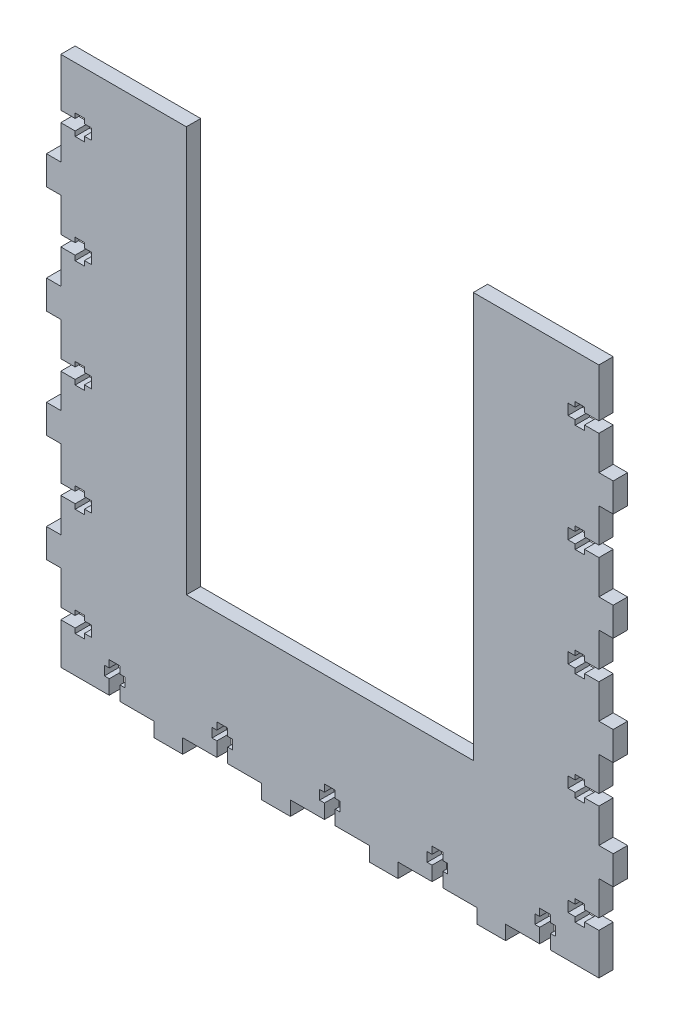
SolidWorks part; units mm, degrees
ref_plane "前视基准面" through (0, 0, 0) normal (0, 0, 1) x (1, 0, 0)
ref_plane "上视基准面" through (0, 0, 0) normal (0, 1, 0) x (1, 0, 0)
ref_plane "右视基准面" through (0, 0, 0) normal (1, 0, 0) x (0, 0, -1)
sketch "草图1" plane through (0, 0, 0) normal (0, 0, 1) x (1, 0, 0)
  line L9 (145, 56.5) -> (149, 56.5)
  line L10 (149, 56.5) -> (149, 55.15)
  line L11 (149, 55.15) -> (151.6, 55.15)
  line L12 (151.6, 55.15) -> (151.6, 56.5)
  line L13 (151.6, 56.5) -> (153.6, 56.5)
  line L14 (153.6, 56.5) -> (153.6, 59.5)
  line L23 (145, 58) -> (143.6922, 58) construction
  line L24 (145, 56.5) -> (145, 47)
  line L25 (151.6, 60.85) -> (151.6, 59.5)
  line L26 (149, 59.5) -> (149, 60.85)
  line L27 (151.6, 59.5) -> (153.6, 59.5)
  line L28 (149, 60.85) -> (151.6, 60.85)
  line L29 (145, 59.5) -> (149, 59.5)
  line L31 (145, 39) -> (141, 39)
  line L32 (141, 39) -> (141, 47)
  line L33 (141, 47) -> (145, 47)
  line L35 (141, 43) -> (142.703, 43) construction
  line L43 (145, 29.5) -> (145, 28) construction
  line L44 (145, 28) -> (143.6922, 28) construction
  line L45 (145, 26.5) -> (149, 26.5)
  line L46 (149, 25.15) -> (151.6, 25.15)
  line L118 (151.6, 26.5) -> (153.6, 26.5)
  line L119 (149, 26.5) -> (149, 25.15)
  line L126 (151.6, 25.15) -> (151.6, 26.5)
  line L127 (153.6, 29.5) -> (153.6, 26.5)
  line L128 (151.6, 29.5) -> (153.6, 29.5)
  line L129 (151.6, 30.85) -> (151.6, 29.5)
  line L130 (149, 30.85) -> (151.6, 30.85)
  line L131 (149, 29.5) -> (149, 30.85)
  line L132 (145, 29.5) -> (149, 29.5)
  line L133 (145, 29.5) -> (145, 39)
  line L134 (141, 13) -> (142.703, 13) construction
  line L135 (141, 9) -> (145, 9)
  line L136 (141, 17) -> (141, 9)
  line L137 (145, 17) -> (141, 17)
  line L138 (145, 26.5) -> (145, 17)
  line L139 (145, -3.5) -> (149, -3.5)
  line L140 (141, 103) -> (142.703, 103) construction
  line L141 (145, 88) -> (143.6922, 88) construction
  line L142 (145, 86.5) -> (145, 88) construction
  line L143 (141, 73) -> (142.703, 73) construction
  line L144 (145, 119.5) -> (145, 133)
  line L145 (145, 107) -> (145, 116.5)
  line L146 (145, 116.5) -> (149, 116.5)
  line L147 (149, 115.15) -> (151.6, 115.15)
  line L148 (151.6, 116.5) -> (153.6, 116.5)
  line L149 (149, 116.5) -> (149, 115.15)
  line L150 (151.6, 115.15) -> (151.6, 116.5)
  line L151 (153.6, 119.5) -> (153.6, 116.5)
  line L152 (151.6, 119.5) -> (153.6, 119.5)
  line L153 (151.6, 120.85) -> (151.6, 119.5)
  line L154 (149, 120.85) -> (151.6, 120.85)
  line L155 (149, 119.5) -> (149, 120.85)
  line L156 (151.6, 60.85) -> (151.6, 59.5)
  line L157 (149, 59.5) -> (149, 60.85)
  line L158 (151.6, 59.5) -> (153.6, 59.5)
  line L159 (149, 60.85) -> (151.6, 60.85)
  line L160 (145, 59.5) -> (149, 59.5)
  line L161 (145, 69) -> (145, 59.5)
  line L162 (145, 119.5) -> (149, 119.5)
  line L163 (145, 89.5) -> (145, 99)
  line L164 (145, 99) -> (141, 99)
  line L165 (145, 56.5) -> (149, 56.5)
  line L166 (149, 55.15) -> (151.6, 55.15)
  line L167 (151.6, 56.5) -> (153.6, 56.5)
  line L168 (149, 56.5) -> (149, 55.15)
  line L169 (151.6, 55.15) -> (151.6, 56.5)
  line L170 (151.6, 59.5) -> (153.6, 59.5)
  line L171 (151.6, 60.85) -> (151.6, 59.5)
  line L172 (149, 60.85) -> (151.6, 60.85)
  line L173 (149, 59.5) -> (149, 60.85)
  line L174 (145, 59.5) -> (149, 59.5)
  line L175 (145, 58) -> (220, 58) construction
  line L176 (220, 58) -> (220, 40.131) construction
  line L177 (141, 99) -> (141, 107)
  line L178 (141, 107) -> (145, 107)
  line L179 (145, 86.5) -> (145, 77)
  line L180 (145, 86.5) -> (149, 86.5)
  line L181 (149, 86.5) -> (149, 85.15)
  line L182 (149, 85.15) -> (151.6, 85.15)
  line L183 (151.6, 85.15) -> (151.6, 86.5)
  line L184 (151.6, 86.5) -> (153.6, 86.5)
  line L185 (153.6, 86.5) -> (153.6, 89.5)
  line L186 (151.6, 90.85) -> (151.6, 89.5)
  line L187 (149, 89.5) -> (149, 90.85)
  line L188 (151.6, 89.5) -> (153.6, 89.5)
  line L189 (149, 90.85) -> (151.6, 90.85)
  line L190 (145, 89.5) -> (149, 89.5)
  line L191 (141, 69) -> (145, 69)
  line L192 (141, 77) -> (141, 69)
  line L193 (145, 77) -> (141, 77)
  line L194 (145, 59.5) -> (145, 69)
  line L195 (151.6, 59.5) -> (153.6, 59.5)
  line L197 (151.6, 60.85) -> (151.6, 59.5)
  line L198 (149, 60.85) -> (151.6, 60.85)
  line L199 (149, 59.5) -> (149, 60.85)
  line L200 (145, 59.5) -> (149, 59.5)
  line L201 (299, 73) -> (297.297, 73) construction
  line L202 (295, 86.5) -> (295, 88) construction
  line L203 (295, 88) -> (296.3078, 88) construction
  line L204 (299, 103) -> (297.297, 103) construction
  line L205 (299, 13) -> (297.297, 13) construction
  line L206 (295, 28) -> (296.3078, 28) construction
  line L207 (295, 29.5) -> (295, 28) construction
  line L208 (299, 43) -> (297.297, 43) construction
  line L209 (295, 58) -> (296.3078, 58) construction
  line L210 (145, -3.5) -> (145, -15)
  line L211 (295, 9) -> (295, -0.5)
  line L212 (295, -0.5) -> (291, -0.5)
  line L213 (291, 0.85) -> (288.4, 0.85)
  line L214 (288.4, -0.5) -> (286.4, -0.5)
  line L215 (291, -0.5) -> (291, 0.85)
  line L216 (288.4, 0.85) -> (288.4, -0.5)
  line L217 (286.4, -3.5) -> (286.4, -0.5)
  line L218 (288.4, -3.5) -> (286.4, -3.5)
  line L219 (288.4, -4.85) -> (288.4, -3.5)
  line L220 (291, -4.85) -> (288.4, -4.85)
  line L221 (291, -3.5) -> (291, -4.85)
  line L222 (295, 59.5) -> (291, 59.5)
  line L223 (291, 59.5) -> (291, 60.85)
  line L224 (291, 60.85) -> (288.4, 60.85)
  line L225 (288.4, 60.85) -> (288.4, 59.5)
  line L226 (288.4, 59.5) -> (286.4, 59.5)
  line L227 (295, 59.5) -> (295, 69)
  line L228 (295, 77) -> (299, 77)
  line L229 (299, 77) -> (299, 69)
  line L230 (299, 69) -> (295, 69)
  line L231 (295, 89.5) -> (291, 89.5)
  line L232 (291, 90.85) -> (288.4, 90.85)
  line L233 (288.4, 89.5) -> (286.4, 89.5)
  line L234 (291, 89.5) -> (291, 90.85)
  line L235 (149, -3.5) -> (149, -4.85)
  line L236 (288.4, 90.85) -> (288.4, 89.5)
  line L237 (286.4, 86.5) -> (286.4, 89.5)
  line L238 (288.4, 86.5) -> (286.4, 86.5)
  line L239 (288.4, 85.15) -> (288.4, 86.5)
  line L240 (291, 85.15) -> (288.4, 85.15)
  line L241 (291, 86.5) -> (291, 85.15)
  line L242 (295, 86.5) -> (291, 86.5)
  line L243 (295, 86.5) -> (295, 77)
  line L244 (299, 107) -> (295, 107)
  line L245 (299, 99) -> (299, 107)
  line L246 (295, 59.5) -> (291, 59.5)
  line L247 (291, 59.5) -> (291, 60.85)
  line L248 (291, 60.85) -> (288.4, 60.85)
  line L250 (158.5, -15) -> (145, -15)
  line L251 (171, -15) -> (161.5, -15)
  line L252 (149, -4.85) -> (151.6, -4.85)
  line L253 (151.6, -4.85) -> (151.6, -3.5)
  line L254 (151.6, -3.5) -> (153.6, -3.5)
  line L255 (153.6, -3.5) -> (153.6, -0.5)
  line L256 (151.6, 0.85) -> (151.6, -0.5)
  line L257 (149, -0.5) -> (149, 0.85)
  line L258 (151.6, -0.5) -> (153.6, -0.5)
  line L259 (149, 0.85) -> (151.6, 0.85)
  line L260 (145, -0.5) -> (149, -0.5)
  line L261 (145, 9) -> (145, -0.5)
  line L262 (295, -3.5) -> (295, -15)
  line L263 (288.4, 60.85) -> (288.4, 59.5)
  line L264 (288.4, 59.5) -> (286.4, 59.5)
  line L265 (288.4, 55.15) -> (288.4, 56.5)
  line L266 (291, 56.5) -> (291, 55.15)
  line L267 (288.4, 56.5) -> (286.4, 56.5)
  line L268 (291, 55.15) -> (288.4, 55.15)
  line L269 (295, 56.5) -> (291, 56.5)
  line L270 (295, 99) -> (299, 99)
  line L271 (295, 89.5) -> (295, 99)
  line L272 (295, 119.5) -> (291, 119.5)
  line L273 (295, 69) -> (295, 59.5)
  line L274 (295, 59.5) -> (291, 59.5)
  line L275 (291, 60.85) -> (288.4, 60.85)
  line L276 (288.4, 59.5) -> (286.4, 59.5)
  line L277 (291, 59.5) -> (291, 60.85)
  line L278 (288.4, 60.85) -> (288.4, 59.5)
  line L279 (291, 119.5) -> (291, 120.85)
  line L280 (291, 120.85) -> (288.4, 120.85)
  line L281 (288.4, 120.85) -> (288.4, 119.5)
  line L282 (288.4, 119.5) -> (286.4, 119.5)
  line L283 (286.4, 119.5) -> (286.4, 116.5)
  line L284 (288.4, 115.15) -> (288.4, 116.5)
  line L285 (291, 116.5) -> (291, 115.15)
  line L286 (288.4, 116.5) -> (286.4, 116.5)
  line L287 (291, 115.15) -> (288.4, 115.15)
  line L288 (295, 116.5) -> (291, 116.5)
  line L289 (295, 107) -> (295, 116.5)
  line L290 (295, 119.5) -> (295, 133)
  line L291 (295, -3.5) -> (291, -3.5)
  line L292 (295, 26.5) -> (295, 17)
  line L293 (295, 17) -> (299, 17)
  line L294 (299, 17) -> (299, 9)
  line L295 (299, 9) -> (295, 9)
  line L296 (295, 29.5) -> (295, 39)
  line L297 (295, 29.5) -> (291, 29.5)
  line L298 (291, 29.5) -> (291, 30.85)
  line L299 (291, 30.85) -> (288.4, 30.85)
  line L300 (288.4, 30.85) -> (288.4, 29.5)
  line L301 (288.4, 29.5) -> (286.4, 29.5)
  line L302 (286.4, 29.5) -> (286.4, 26.5)
  line L303 (288.4, 25.15) -> (288.4, 26.5)
  line L304 (291, 26.5) -> (291, 25.15)
  line L305 (288.4, 26.5) -> (286.4, 26.5)
  line L306 (291, 25.15) -> (288.4, 25.15)
  line L307 (295, 26.5) -> (291, 26.5)
  line L308 (299, 47) -> (295, 47)
  line L309 (299, 39) -> (299, 47)
  line L310 (295, 39) -> (299, 39)
  line L311 (295, 59.5) -> (291, 59.5)
  line L312 (291, 60.85) -> (288.4, 60.85)
  line L313 (288.4, 59.5) -> (286.4, 59.5)
  line L314 (291, 59.5) -> (291, 60.85)
  line L315 (288.4, 60.85) -> (288.4, 59.5)
  line L316 (295, 56.5) -> (295, 47)
  line L317 (286.4, 56.5) -> (286.4, 59.5)
  line L318 (288.4, 56.5) -> (286.4, 56.5)
  line L319 (288.4, 55.15) -> (288.4, 56.5)
  line L320 (291, 55.15) -> (288.4, 55.15)
  line L321 (291, 56.5) -> (291, 55.15)
  line L322 (295, 56.5) -> (291, 56.5)
  line L323 (161.5, -15) -> (161.5, -11)
  line L324 (162.85, -11) -> (162.85, -8.4)
  line L325 (161.5, -8.4) -> (161.5, -6.4)
  line L326 (161.5, -11) -> (162.85, -11)
  line L327 (162.85, -8.4) -> (161.5, -8.4)
  line L328 (158.5, -6.4) -> (161.5, -6.4)
  line L329 (158.5, -8.4) -> (158.5, -6.4)
  line L330 (157.15, -8.4) -> (158.5, -8.4)
  line L331 (157.15, -11) -> (157.15, -8.4)
  line L332 (158.5, -11) -> (157.15, -11)
  line L333 (221.5, -15) -> (221.5, -11)
  line L334 (221.5, -11) -> (222.85, -11)
  line L335 (222.85, -11) -> (222.85, -8.4)
  line L336 (222.85, -8.4) -> (221.5, -8.4)
  line L337 (221.5, -8.4) -> (221.5, -6.4)
  line L338 (221.5, -15) -> (231, -15)
  line L339 (239, -15) -> (239, -19)
  line L340 (239, -19) -> (231, -19)
  line L341 (231, -19) -> (231, -15)
  line L342 (251.5, -15) -> (251.5, -11)
  line L343 (252.85, -11) -> (252.85, -8.4)
  line L344 (251.5, -8.4) -> (251.5, -6.4)
  line L345 (251.5, -11) -> (252.85, -11)
  line L346 (252.85, -8.4) -> (251.5, -8.4)
  line L347 (248.5, -6.4) -> (251.5, -6.4)
  line L348 (248.5, -8.4) -> (248.5, -6.4)
  line L349 (247.15, -8.4) -> (248.5, -8.4)
  line L350 (247.15, -11) -> (247.15, -8.4)
  line L351 (248.5, -11) -> (247.15, -11)
  line L352 (248.5, -15) -> (248.5, -11)
  line L353 (248.5, -15) -> (239, -15)
  line L354 (269, -19) -> (269, -15)
  line L355 (261, -19) -> (269, -19)
  line L356 (221.5, -15) -> (221.5, -11)
  line L357 (221.5, -11) -> (222.85, -11)
  line L358 (222.85, -11) -> (222.85, -8.4)
  line L359 (222.85, -8.4) -> (221.5, -8.4)
  line L360 (221.5, -8.4) -> (221.5, -6.4)
  line L361 (217.15, -8.4) -> (218.5, -8.4)
  line L362 (218.5, -11) -> (217.15, -11)
  line L363 (218.5, -8.4) -> (218.5, -6.4)
  line L364 (217.15, -11) -> (217.15, -8.4)
  line L365 (218.5, -15) -> (218.5, -11)
  line L366 (261, -15) -> (261, -19)
  line L367 (251.5, -15) -> (261, -15)
  line L368 (281.5, -15) -> (281.5, -11)
  line L369 (231, -15) -> (221.5, -15)
  line L370 (221.5, -15) -> (221.5, -11)
  line L371 (222.85, -11) -> (222.85, -8.4)
  line L372 (221.5, -8.4) -> (221.5, -6.4)
  line L373 (221.5, -11) -> (222.85, -11)
  line L374 (222.85, -8.4) -> (221.5, -8.4)
  line L375 (281.5, -11) -> (282.85, -11)
  line L376 (282.85, -11) -> (282.85, -8.4)
  line L377 (282.85, -8.4) -> (281.5, -8.4)
  line L378 (281.5, -8.4) -> (281.5, -6.4)
  line L379 (281.5, -6.4) -> (278.5, -6.4)
  line L380 (277.15, -8.4) -> (278.5, -8.4)
  line L381 (278.5, -11) -> (277.15, -11)
  line L382 (278.5, -8.4) -> (278.5, -6.4)
  line L383 (277.15, -11) -> (277.15, -8.4)
  line L384 (278.5, -15) -> (278.5, -11)
  line L385 (269, -15) -> (278.5, -15)
  line L386 (281.5, -15) -> (295, -15)
  line L387 (158.5, -15) -> (158.5, -11)
  line L388 (188.5, -15) -> (179, -15)
  line L389 (179, -15) -> (179, -19)
  line L390 (179, -19) -> (171, -19)
  line L391 (171, -19) -> (171, -15)
  line L392 (191.5, -15) -> (201, -15)
  line L393 (191.5, -15) -> (191.5, -11)
  line L394 (191.5, -11) -> (192.85, -11)
  line L395 (192.85, -11) -> (192.85, -8.4)
  line L396 (192.85, -8.4) -> (191.5, -8.4)
  line L397 (191.5, -8.4) -> (191.5, -6.4)
  line L398 (191.5, -6.4) -> (188.5, -6.4)
  line L399 (187.15, -8.4) -> (188.5, -8.4)
  line L400 (188.5, -11) -> (187.15, -11)
  line L401 (188.5, -8.4) -> (188.5, -6.4)
  line L402 (187.15, -11) -> (187.15, -8.4)
  line L403 (188.5, -15) -> (188.5, -11)
  line L404 (209, -19) -> (209, -15)
  line L405 (201, -19) -> (209, -19)
  line L406 (201, -15) -> (201, -19)
  line L407 (221.5, -15) -> (221.5, -11)
  line L408 (222.85, -11) -> (222.85, -8.4)
  line L409 (221.5, -8.4) -> (221.5, -6.4)
  line L410 (221.5, -11) -> (222.85, -11)
  line L411 (222.85, -8.4) -> (221.5, -8.4)
  line L412 (218.5, -15) -> (209, -15)
  line L413 (218.5, -6.4) -> (221.5, -6.4)
  line L414 (218.5, -8.4) -> (218.5, -6.4)
  line L415 (217.15, -8.4) -> (218.5, -8.4)
  line L416 (217.15, -11) -> (217.15, -8.4)
  line L417 (218.5, -11) -> (217.15, -11)
  line L418 (218.5, -15) -> (218.5, -11)
  line L419 (235, -19) -> (235, -17.297) construction
  line L420 (248.5, -15) -> (250, -15) construction
  line L421 (250, -15) -> (250, -16.3078) construction
  line L422 (265, -19) -> (265, -17.297) construction
  line L423 (175, -19) -> (175, -17.297) construction
  line L424 (190, -15) -> (190, -16.3078) construction
  line L425 (191.5, -15) -> (190, -15) construction
  line L426 (205, -19) -> (205, -17.297) construction
  line L427 (220, -15) -> (220, -16.3078) construction
  line L430 (145, 133) -> (295, 133)
  point P15 (144.3461, 58)
  dimension "D2" = 15
  dimension "D12" = 75
  dimension "D3" = 4
  dimension "D4" = 2
  dimension "D5" = 2.6
  dimension "D6" = 1.35
  dimension "D8" = 1.5
  dimension "D9" = 4
  dimension "D10" = 8
  dimension "D11" = 75
extrude "凸台-拉伸1" add sketch "草图1" along normal blind 4
sketch "草图3" plane through (145, 0, 0) normal (-1, 0, 0) x (0, 0, 1)
  line L0 (2, -3.5) -> (2, -0.5)
  line L1 (4, -3.5) -> (0, -3.5) construction
  line L2 (4, -0.5) -> (0, -0.5) construction
  circle A0 centre (2, -2) radius 1.5
sketch "草图4" plane through (0, 0, 0) normal (0, 0, -1) x (-1, 0, 0)
  line L0 (-145, 133) -> (-295, 133) construction
  line L1 (-260, 133) -> (-180, 133)
  line L2 (-260, 133) -> (-260, 20)
  line L3 (-260, 20) -> (-180, 20)
  line L4 (-180, 133) -> (-180, 20)
  line L5 (-295, 119.5) -> (-295, 133) construction
  line L6 (-145, 89.5) -> (-145, 99) construction
  line L7 (-218.5, -15) -> (-209, -15) construction
  point P6 (-183.6416, 10.0404)
  point P11 (-145, 94.25)
  dimension "D1" = 35
  dimension "D2" = 35
  dimension "D3" = 35
extrude "切除-拉伸1" cut sketch "草图4" against normal blind 4
